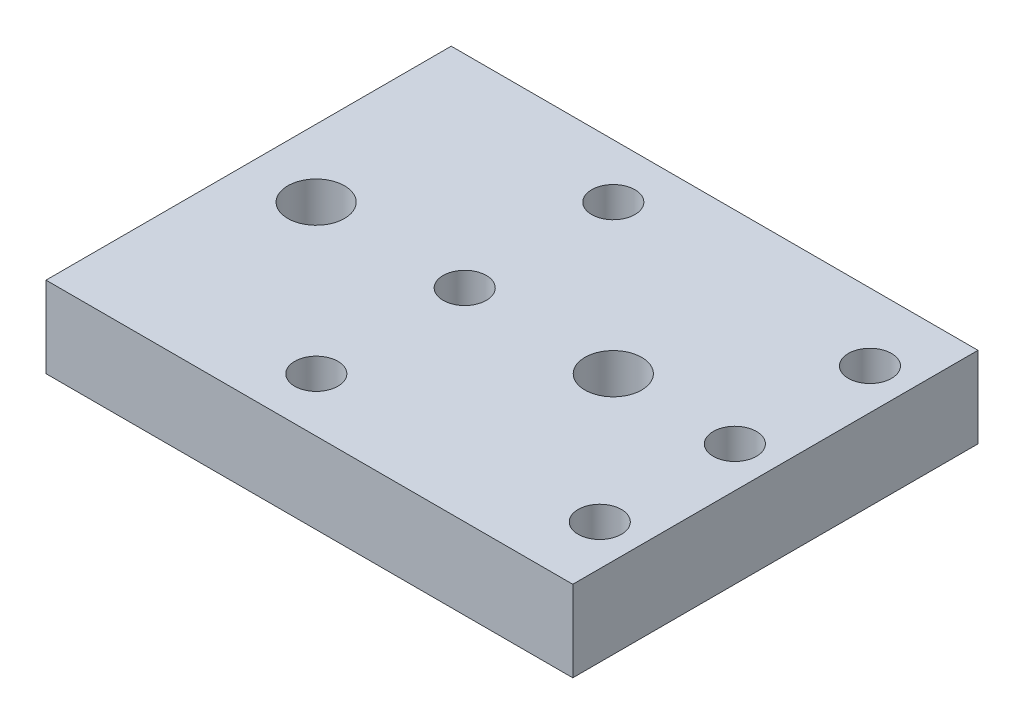
SolidWorks part; units mm, degrees
ref_plane "前视基准面" through (0, 0, 0) normal (0, 0, 1) x (1, 0, 0)
ref_plane "上视基准面" through (0, 0, 0) normal (0, 1, 0) x (1, 0, 0)
ref_plane "右视基准面" through (0, 0, 0) normal (1, 0, 0) x (0, 0, -1)
other "Configuration Table"
sketch "草图1" plane through (0, 0, 0) normal (0, 1, 0) x (1, 0, 0)
  line L0 (16, 15) -> (50015.994, 39.5279) construction
  line L1 (0, 0) -> (39, 0)
  line L2 (0, 0) -> (0, 30)
  line L3 (0, 30) -> (39, 30)
  line L4 (39, 0) -> (39, 30)
  line L5 (16, 15) -> (16, 50015) construction
  circle A0 centre (16, 15) radius 11 construction
  circle A1 centre (16, 15) radius 1.6
  circle A2 centre (16, 26) radius 1.6
  circle A3 centre (5, 15) radius 2.1
  circle A4 centre (16.0108, 4) radius 1.6
  circle A5 centre (27, 15) radius 2.1
  circle A6 centre (36, 25) radius 1.6
  circle A7 centre (36, 15) radius 1.6
  circle A8 centre (36, 5) radius 1.6
  dimension "D3" = 22
  dimension "D6" = 3.2
  dimension "D7" = 3.2
  dimension "D8" = 4.2
  dimension "D9" = 3.2
  dimension "D10" = 5
  dimension "D12" = 3
  dimension "D1" = 30
  dimension "D2" = 39
  dimension "D4" = 16
  dimension "D5" = 15
  dimension "D11" = 3
extrude "凸台-拉伸1" add sketch "草图1" along normal blind 6
